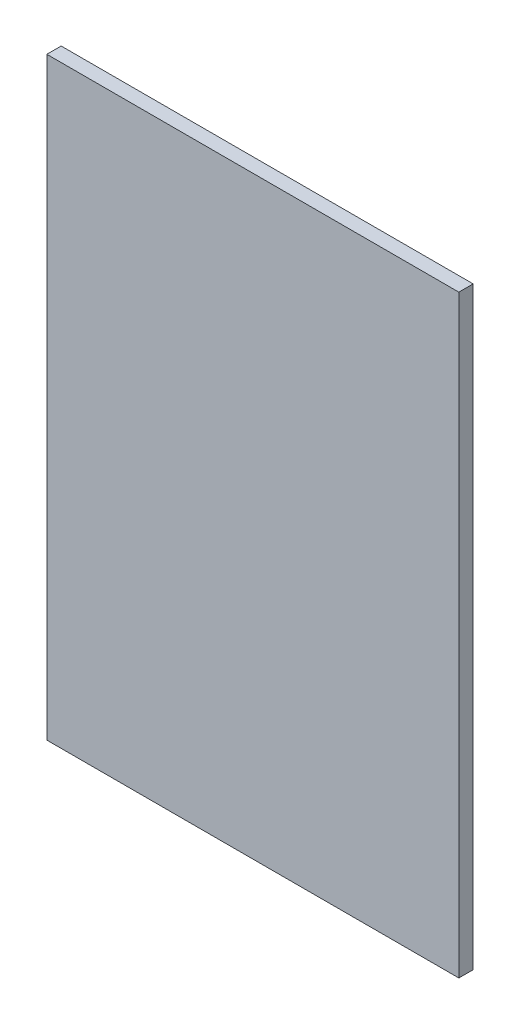
SolidWorks part; units mm, degrees
ref_plane "Front Plane" through (0, 0, 0) normal (0, 0, 1) x (1, 0, 0)
ref_plane "Top Plane" through (0, 0, 0) normal (0, 1, 0) x (1, 0, 0)
ref_plane "Right Plane" through (0, 0, 0) normal (1, 0, 0) x (0, 0, -1)
sketch "Sketch1" plane through (0, 0, 0) normal (0, 0, 1) x (1, 0, 0)
  line L0 (489, -28) -> (489, -733) construction
  line L1 (0, -733) -> (489, -733) construction
  line L2 (0, -28) -> (0, -733) construction
  line L3 (0, -28) -> (489, -28) construction
  line L4 (489, -28) -> (489, -733)
  line L5 (0, -733) -> (489, -733)
  line L6 (0, -28) -> (0, -733)
  line L7 (0, -28) -> (489, -28)
extrude "Boss-Extrude1" add sketch "Sketch1" along normal blind 17
